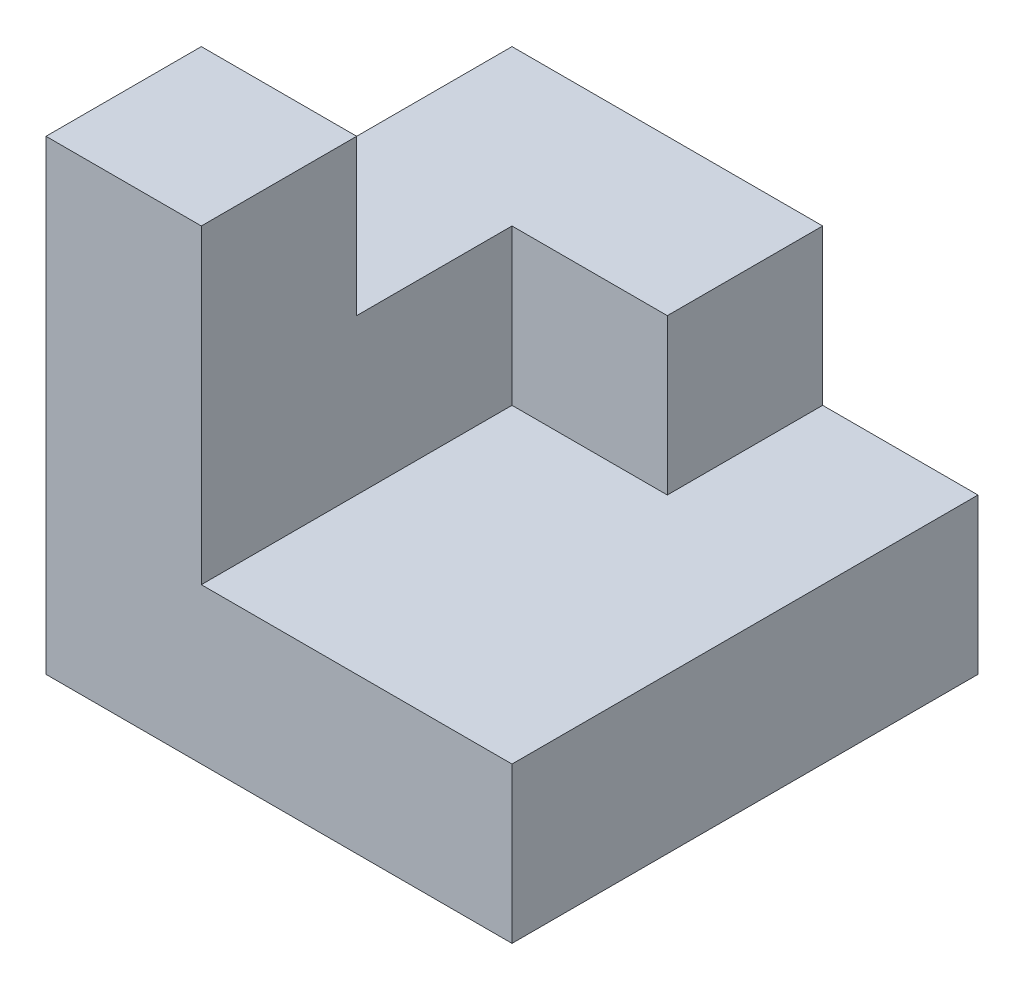
SolidWorks part; units mm, degrees
ref_plane "Alzado" through (0, 0, 0) normal (0, 0, 1) x (1, 0, 0)
ref_plane "Planta" through (0, 0, 0) normal (0, 1, 0) x (1, 0, 0)
ref_plane "Vista lateral" through (0, 0, 0) normal (1, 0, 0) x (0, 0, -1)
sketch "Croquis1" plane through (0, 0, 0) normal (0, 1, 0) x (1, 0, 0)
  line L1 (-30, 30) -> (30, 30)
  line L2 (-30, 30) -> (-30, -30)
  line L3 (-30, -30) -> (30, -30)
  line L4 (30, 30) -> (30, -30)
  line L5 (-30, 30) -> (30, -30) construction
  line L6 (-30, -30) -> (30, 30) construction
  point P0 (0, 0)
  dimension "D1" = 60
  dimension "D2" = 60
extrude "Saliente-Extruir1" add sketch "Croquis1" along normal blind 20
sketch "Croquis2" plane through (0, 20, 0) normal (0, 1, 0) x (1, 0, 0)
  line L0 (-30, -30) -> (-10, -30)
  line L1 (-30, -30) -> (30, -30) construction
  line L2 (-10, -30) -> (-10, 10)
  line L3 (-10, 10) -> (10, 10)
  line L4 (10, 10) -> (10, 30)
  line L5 (30, 30) -> (-30, 30) construction
  line L6 (-30, 30) -> (-30, -30)
  line L7 (-30, 30) -> (10, 30)
  dimension "D1" = 40
  dimension "D2" = 20
  dimension "D3" = 20
extrude "Saliente-Extruir2" add sketch "Croquis2" along normal blind 20
sketch "Croquis3" plane through (0, 40, 0) normal (0, 1, 0) x (1, 0, 0)
  line L0 (-30, 30) -> (-30, -30) construction
  line L1 (-30, -30) -> (-10, -30)
  line L2 (-30, -30) -> (-30, -10)
  line L3 (-30, -10) -> (-10, -10)
  line L4 (-10, -30) -> (-10, -10)
  line L5 (-10, -30) -> (-10, 10) construction
  dimension "D1" = 20
extrude "Saliente-Extruir3" add sketch "Croquis3" along normal blind 20
